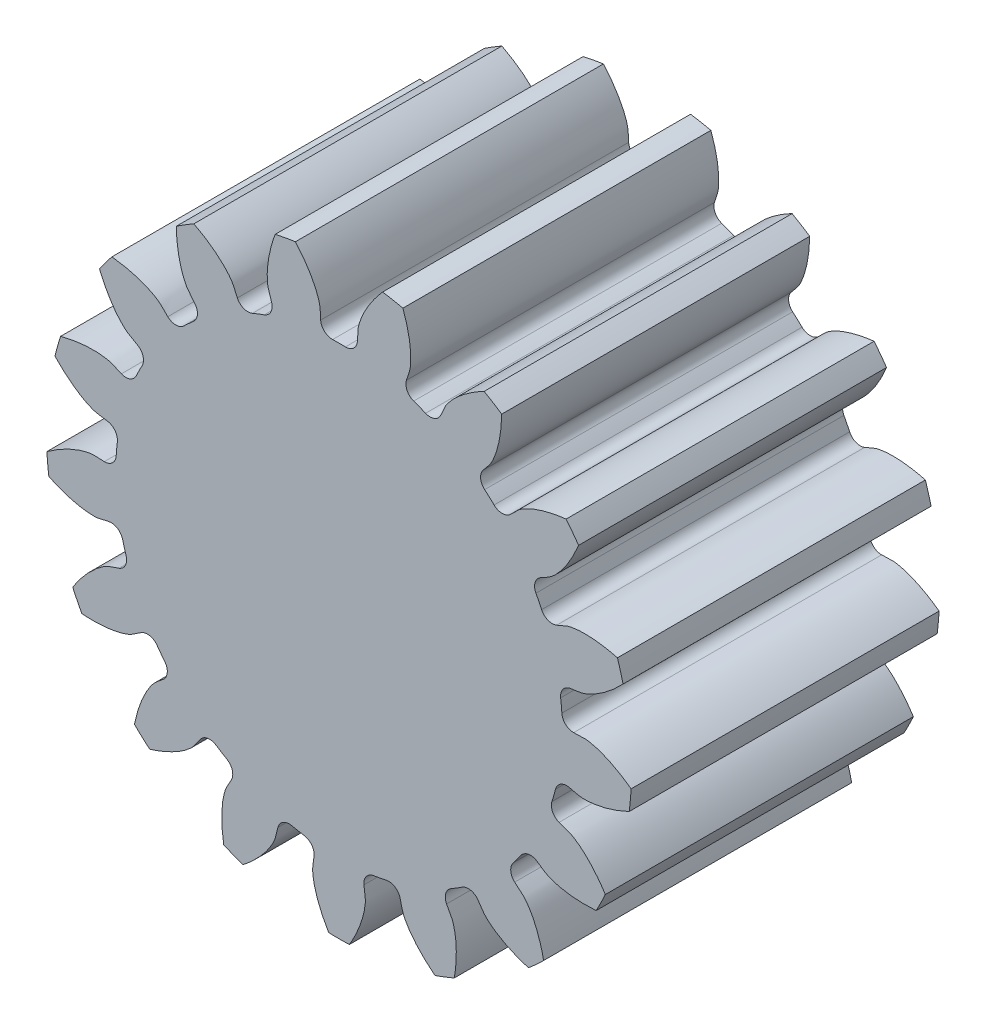
SolidWorks part; units mm, degrees
ref_plane "前视基准面" through (0, 0, 0) normal (0, 0, 1) x (1, 0, 0)
ref_plane "上视基准面" through (0, 0, 0) normal (0, 1, 0) x (1, 0, 0)
ref_plane "右视基准面" through (0, 0, 0) normal (1, 0, 0) x (0, 0, -1)
other "Configuration Table"
ref_axis "Axis1" through (0, 0, -88.99) along (0, 0, 1)
sketch "草图1" plane through (0, 0, 0) normal (0, 0, 1) x (1, 0, 0)
  circle A0 centre (0, 0) radius 9.5
extrude "LaShenA" add sketch "草图1" along normal blind 10
sketch "SketchA" plane through (0, 0, 10) normal (0, 0, 1) x (1, 0, 0)
  line L0 (0, 0) -> (0, 9.5) construction
  arc A0 (0.207, 7.247) -> (-0.207, 7.247) centre (0, 0) ccw
  arc A1 (1.9284, 9.9057) -> (-1.9284, 9.9057) centre (0, 0) ccw
  arc A2 (-0.207, 7.247) -> (-0.5968, 7.5982) centre (-0.2179, 7.6269) cw
  arc A3 (0.5968, 7.5982) -> (0.207, 7.247) centre (0.2179, 7.6269) cw
  circle A4 centre (0, 0) radius 7.9874 construction
  circle A5 centre (0, 0) radius 9.5 construction
  circle A6 centre (0, 0) radius 7.25 construction
  circle A7 centre (0, 0) radius 8.5 construction
  spline S0 degree 3 poles (0.5968, 7.5982) (0.606, 7.7206) (0.6026, 7.8698) (0.6296, 8.029) (0.6422, 8.0808) (0.6533, 8.1218) (0.6675, 8.1687) (0.685, 8.2214) (0.7063, 8.2797) (0.7317, 8.3435) (0.7614, 8.4125) (0.7959, 8.4865) (0.8354, 8.5654) (0.8802, 8.6489) (0.9307, 8.7367) (0.987, 8.8286) (1.0495, 8.9244) (1.1185, 9.0236) (1.1941, 9.1262) (1.2767, 9.2316) (1.3664, 9.3397) (1.4635, 9.4501) (1.5682, 9.5624) (1.7212, 9.7175) (1.8433, 9.8309) (1.9284, 9.9057) knots 0.121184 0.121184 0.121184 0.121184 0.238206 0.264317 0.275812 0.289397 0.305072 0.322837 0.342692 0.364637 0.388672 0.414798 0.443013 0.473318 0.505713 0.540198 0.576773 0.615438 0.656194 0.699039 0.743974 0.790999 0.840114 0.89132 1 1 1 1
  spline S1 degree 3 poles (-0.5968, 7.5982) (-0.606, 7.7206) (-0.6026, 7.8698) (-0.6296, 8.029) (-0.6422, 8.0808) (-0.6533, 8.1218) (-0.6675, 8.1687) (-0.685, 8.2214) (-0.7063, 8.2797) (-0.7317, 8.3435) (-0.7614, 8.4125) (-0.7959, 8.4865) (-0.8354, 8.5654) (-0.8802, 8.6489) (-0.9307, 8.7367) (-0.987, 8.8286) (-1.0495, 8.9244) (-1.1185, 9.0236) (-1.1941, 9.1262) (-1.2767, 9.2316) (-1.3664, 9.3397) (-1.4635, 9.4501) (-1.5682, 9.5624) (-1.7212, 9.7175) (-1.8433, 9.8309) (-1.9284, 9.9057) knots 0.121184 0.121184 0.121184 0.121184 0.238206 0.264317 0.275812 0.289397 0.305072 0.322837 0.342692 0.364637 0.388672 0.414798 0.443013 0.473318 0.505713 0.540198 0.576773 0.615438 0.656194 0.699039 0.743974 0.790999 0.840114 0.89132 1 1 1 1
  dimension "D1" = 0.38
  dimension "Db" = 15.9748
  dimension "Da" = 19
  dimension "Df" = 14.5
  dimension "Dn" = 17
extrude "Cut-ExtrudeA" cut sketch "SketchA" against normal blind 30
pattern_circular "www.KYTool.cn" count 17 over 360 about axis through (0, 0, -88.99) along (0, 0, 1) of "Cut-ExtrudeA"
